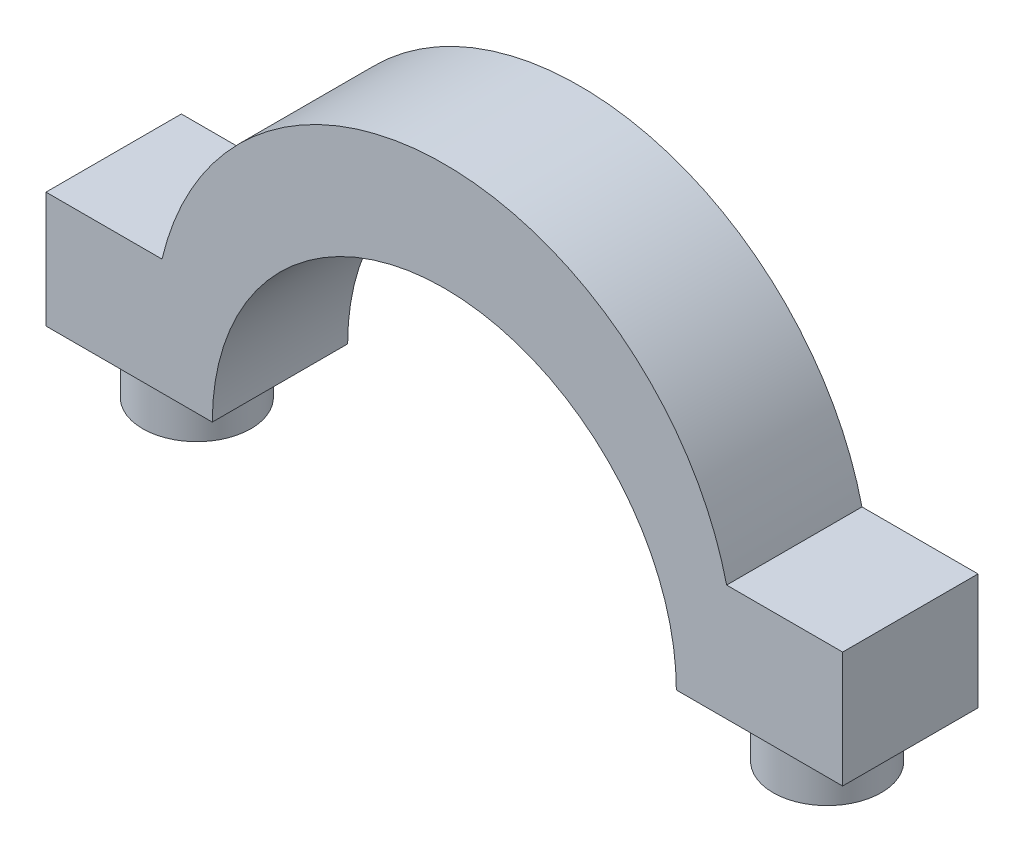
SolidWorks part; units mm, degrees
ref_plane "Front Plane" through (0, 0, 0) normal (0, 0, 1) x (1, 0, 0)
ref_plane "Top Plane" through (0, 0, 0) normal (0, 1, 0) x (1, 0, 0)
ref_plane "Right Plane" through (0, 0, 0) normal (1, 0, 0) x (0, 0, -1)
sketch "Sketch2" plane through (0, 0, 0) normal (0, 0, 1) x (1, 0, 0)
  line L0 (-22.1848, 0) -> (8.2952, 0) construction
  line L1 (19.2172, 0) -> (-33.1068, 0) construction
  line L2 (-6.9448, 4.2361) -> (-6.9448, -14.8833) construction
  line L3 (-22.1848, 0) -> (-33.1068, 0)
  line L4 (-33.1068, 0) -> (-33.1068, 7.62)
  line L5 (-33.1068, 7.62) -> (-25.4868, 7.62)
  line L6 (19.2172, 7.62) -> (11.5972, 7.62)
  line L7 (8.2952, 0) -> (19.2172, 0)
  line L8 (19.2172, 0) -> (19.2172, 7.62)
  arc A0 (-22.1848, 0) -> (8.2952, 0) centre (-6.9448, 0) cw
  arc A1 (-25.4868, 7.62) -> (11.5972, 7.62) centre (-6.9448, 3.25) cw
  dimension "D2" = 15.24
  dimension "D6" = 19.05
  dimension "D1" = 30.48
  dimension "D3" = 26.162
  dimension "D4" = 7.62
  dimension "D5" = 7.62
extrude "Boss-Extrude1" add sketch "Sketch2" along normal blind 8.89
sketch "Sketch3" plane through (0, 0, 0) normal (0, -1, 0) x (1, 0, 0)
  line L3 (-27.6458, 8.89) -> (-27.6458, 0) construction
  line L4 (-33.1068, 8.89) -> (-22.1848, 8.89) construction
  line L5 (-33.1068, 0) -> (-22.1848, 0) construction
  line L6 (-6.9448, 8.89) -> (-6.9448, -1.2229) construction
  line L7 (8.2952, 8.89) -> (-22.1848, 8.89) construction
  circle A0 centre (-27.6458, 4.445) radius 3.556
  circle A1 centre (13.7562, 4.445) radius 3.556
  dimension "D1" = 7.112
extrude "Boss-Extrude2" add sketch "Sketch3" along normal blind 3.556
